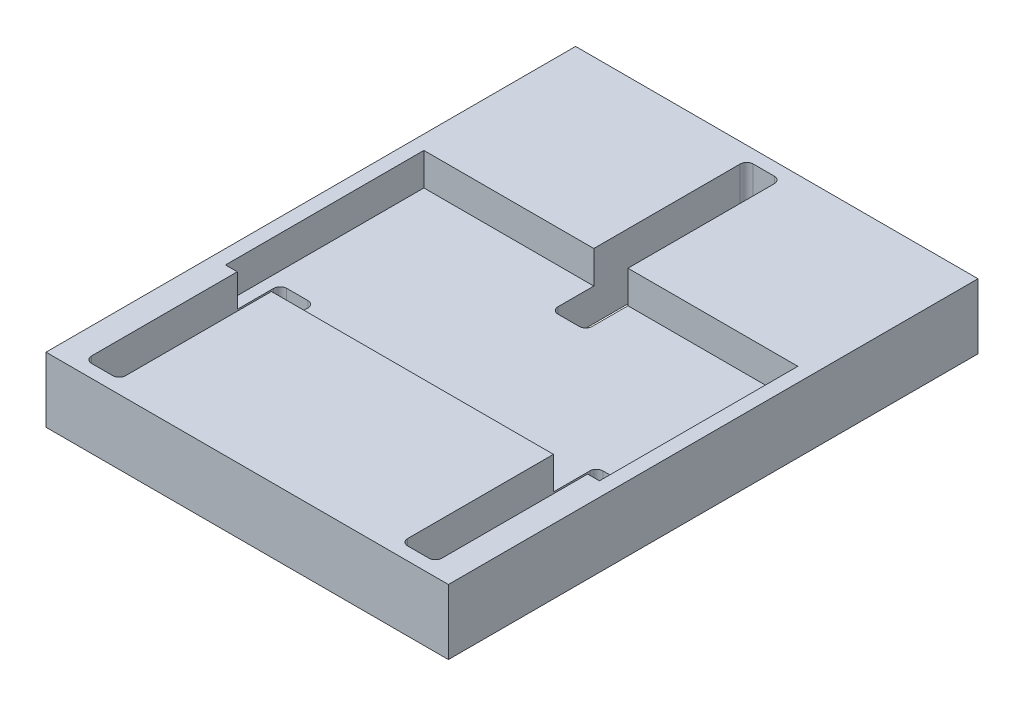
SolidWorks part; units mm, degrees
ref_plane "Front Plane" through (0, 0, 0) normal (0, 0, 1) x (1, 0, 0)
ref_plane "Top Plane" through (0, 0, 0) normal (0, 1, 0) x (1, 0, 0)
ref_plane "Right Plane" through (0, 0, 0) normal (1, 0, 0) x (0, 0, -1)
sketch "00 state" plane through (0, 0, 0) normal (0, 1, 0) x (1, 0, 0)
  line L0 (0, 0) -> (0, 15)
  line L1 (0, 15) -> (11.8, 31.1481)
  line L2 (11.8, 31.1481) -> (36.8, 31.1481)
  line L3 (36.8, 31.1481) -> (48.6, 15)
  line L4 (48.6, 15) -> (48.6, 0)
  line L5 (11.8, 31.1481) -> (24.3, 39.9007)
  line L6 (24.3, 39.9007) -> (36.8, 31.1481)
  line L7 (24.3, 39.9007) -> (24.3, 47.4007)
  line L8 (24.3, 47.4007) -> (24.3, 62.4007)
  dimension "D1" = 35
  dimension "D2" = 7.5
  dimension "D3" = 15
  dimension "D4" = 15
  dimension "D5" = 20
  dimension "D6" = 25
  dimension "D7" = 0
  dimension "D8" = 48.6
  dimension "D9" = 24.3
sketch "01 state" plane through (0, 0, 0) normal (0, 1, 0) x (1, 0, 0)
  line L0 (0, 0) -> (0, 15)
  line L1 (0, 15) -> (5.8095, 34.1377)
  line L2 (5.8095, 34.1377) -> (30.8095, 34.1377)
  line L3 (30.8095, 34.1377) -> (48.6, 25)
  line L4 (48.6, 25) -> (48.6, 10)
  line L5 (5.8095, 34.1377) -> (18.3095, 42.8903)
  line L6 (18.3095, 42.8903) -> (30.8095, 34.1377)
  line L7 (18.3095, 42.8903) -> (24.3, 47.4028)
  line L8 (24.3, 47.4028) -> (24.3, 62.4028)
  point P3 (37.9019, 64.6686)
  point P11 (0, 0)
  dimension "D1" = 35
  dimension "D2" = 7.5
  dimension "D3" = 15
  dimension "D4" = 15
  dimension "D5" = 20
  dimension "D6" = 25
  dimension "D7" = 48.6
  dimension "D8" = 24.3
  dimension "D9" = 10
sketch "10 state" plane through (0, 0, 0) normal (0, 1, 0) x (1, 0, 0)
  line L0 (0, 10) -> (0, 25)
  line L1 (0, 25) -> (17.7905, 34.1377)
  line L2 (17.7905, 34.1377) -> (42.7905, 34.1377)
  line L3 (42.7905, 34.1377) -> (48.6, 15)
  line L4 (48.6, 15) -> (48.6, 0)
  line L5 (17.7905, 34.1377) -> (30.2905, 42.8903)
  line L6 (30.2905, 42.8903) -> (42.7905, 34.1377)
  line L7 (30.2905, 42.8903) -> (24.3, 47.4028)
  line L8 (24.3, 47.4028) -> (24.3, 62.4028)
  point P3 (24.5104, 73.8516)
  dimension "D3" = 15
  dimension "D8" = 48.6
  dimension "D9" = 24.3
  dimension "D1" = 7.5
  dimension "D2" = 10
  dimension "D4" = 20
  dimension "D5" = 25
  dimension "D6" = 35
  dimension "D7" = 15
  dimension "D10" = 0
sketch "11 state" plane through (0, 0, 0) normal (0, 1, 0) x (1, 0, 0)
  line L0 (0, 10) -> (0, 25)
  line L1 (0, 25) -> (11.8, 41.1481)
  line L2 (11.8, 41.1481) -> (36.8, 41.1481)
  line L3 (36.8, 41.1481) -> (48.6, 25)
  line L4 (48.6, 25) -> (48.6, 10)
  line L5 (11.8, 41.1481) -> (24.3, 49.9007)
  line L6 (24.3, 49.9007) -> (36.8, 41.1481)
  line L7 (24.3, 49.9007) -> (24.3, 57.4007)
  line L8 (24.3, 57.4007) -> (24.3, 72.4007)
  point P3 (31.7394, 84.623)
  point P11 (66.091, 27.3101)
  dimension "D2" = 7.5
  dimension "D4" = 20
  dimension "D1" = 25
  dimension "D3" = 35
  dimension "D5" = 15
  dimension "D6" = 15
  dimension "D7" = 10
  dimension "D8" = 10
  dimension "D9" = 48.6
  dimension "D10" = 24.3
sketch "Sketch15" plane through (0, 0, 0) normal (0, 1, 0) x (1, 0, 0)
  line L0 (24.3, 76.9007) -> (-6.625, 76.9007)
  line L1 (-6.625, 76.9007) -> (-6.625, -4.5)
  line L2 (-6.625, -4.5) -> (24.3, -4.5)
  line L3 (24.3, -4.5) -> (24.3, 44.9007)
  line L4 (21.675, 72.4007) -> (21.675, 47.4007)
  line L5 (24.3, 44.9007) -> (21.675, 44.9007)
  line L6 (21.675, 44.9007) -> (21.675, 47.4007)
  line L7 (24.3, 74.9007) -> (21.675, 74.9007)
  line L8 (21.675, 74.9007) -> (21.675, 72.4007)
  line L9 (24.3, 69.7757) -> (24.3, 69.9007)
  line L10 (24.3, 74.9007) -> (24.3, 76.9007)
  line L11 (24.3, 49.9007) -> (24.3, 50.0257)
  line L12 (-2.625, 25) -> (-2.625, 0)
  line L13 (2.625, 25) -> (2.625, 0)
  line L14 (0, 27.5) -> (-2.625, 27.5)
  line L15 (-2.625, 27.5) -> (-2.625, 25)
  line L16 (0, 27.5) -> (2.625, 27.5)
  line L17 (2.625, 27.5) -> (2.625, 25)
  line L18 (0, -2.5) -> (2.625, -2.5)
  line L19 (2.625, -2.5) -> (2.625, 0)
  line L20 (0, -2.5) -> (-2.625, -2.5)
  line L21 (-2.625, -2.5) -> (-2.625, 0)
  circle A0 centre (24.3, 72.4007) radius 2.625 construction
  circle A1 centre (24.3, 72.4007) radius 2.5 construction
  circle A2 centre (24.3, 47.4007) radius 2.625 construction
  circle A3 centre (24.3, 47.4007) radius 2.5 construction
  circle A4 centre (0, 0) radius 2.625 construction
  circle A5 centre (0, 0) radius 2.5 construction
  circle A6 centre (0, 25) radius 2.625 construction
  circle A7 centre (0, 25) radius 2.5 construction
  point P39 (2.625, 25)
  dimension "D1" = 5.25
  dimension "D2" = 5
  dimension "D3" = 2
  dimension "D4" = 2
  dimension "D5" = 4
extrude "Boss-Extrude5" add sketch "Sketch15" along normal blind 10 contours L2 L3 L5 L6 L4 L8 L7 L10 L0 L1 | L13 L19 L18 L20 L21 L12 L15 L14 L16 L17
sketch "Sketch18" plane through (0, 10, 0) normal (0, 1, 0) x (1, 0, 0)
  line L0 (11.8, 41.1481) -> (11.8, 51.3981) construction
  line L1 (5.8095, 34.1377) -> (-4.4405, 34.1377) construction
  line L2 (11.8, 31.1481) -> (11.8, 20.8981) construction
  line L3 (21.675, 51.3981) -> (-4.4405, 51.3981)
  line L4 (21.675, 44.9007) -> (21.675, 74.9007) construction
  line L5 (-4.4405, 51.3981) -> (-4.4405, 20.8981)
  line L6 (-4.4405, 20.8981) -> (24.3, 20.8981)
  line L7 (24.3, -4.5) -> (24.3, 44.9007) construction
  line L8 (24.3, 20.8981) -> (24.3, 51.3981)
  line L10 (24.3, 51.3981) -> (21.675, 51.3981)
  point P13 (0, 0)
  dimension "D1" = 10.25
  dimension "D2" = 10.25
  dimension "D3" = 10.25
  dimension "D4" = 30.5
extrude "Cut-Extrude6" cut sketch "Sketch18" against normal blind 5
fillet "Fillet4" radius 1 6 edges at (2.625, 5, 2.5) (-2.625, 5, 2.5) (2.625, 2.5, -27.5) (-2.625, 2.5, -27.5) (21.675, 2.5, -44.9007) (21.675, 5, -74.9007)
mirror "Mirror25" about plane through (24.3, 10, 4.5) normal (-1, 0, 0) of "Fillet4", "Cut-Extrude6", "Boss-Extrude5"
sketch "Sketch19" plane through (0, 10, 0) normal (0, 1, 0) x (1, 0, 0)
  line L0 (2.625, 20.8981) -> (2.625, 26.5) construction
  line L1 (-1.625, 27.5) -> (1.625, 27.5) construction
  line L2 (-2.625, 26.5) -> (-2.625, 20.8981) construction
  line L3 (2.625, 21.1481) -> (2.625, 26.5)
  line L4 (-1.625, 27.5) -> (1.625, 27.5)
  line L5 (-2.625, 26.5) -> (-2.625, 21.1481)
  line L6 (-2.625, 21.1481) -> (-4.3405, 21.1481)
  line L7 (-4.3405, 21.1481) -> (-4.3405, 41.1481)
  line L8 (-4.3405, 41.1481) -> (24.3, 41.1481)
  line L9 (24.3, 41.1481) -> (24.3, 33.7731)
  line L10 (24.3, 21.1481) -> (2.625, 21.1481)
  line L11 (24.3, 76.9007) -> (24.3, 33.7731) construction
  line L12 (55.225, 76.9007) -> (-6.625, 76.9007) construction
  line L13 (-6.625, -4.5) -> (55.225, -4.5) construction
  line L14 (2.625, 20.8981) -> (45.975, 20.8981) construction
  line L15 (-4.4405, 51.3981) -> (-4.4405, 20.8981) construction
  line L16 (24.3, 31.1481) -> (-4.3405, 31.1481) construction
  line L17 (0.6595, 33.7731) -> (24.3, 33.7731)
  line L18 (0.6595, 28.5231) -> (24.3, 28.5231)
  line L19 (24.3, 28.5231) -> (24.3, 21.1481)
  line L20 (24.3, 28.5231) -> (24.3, -4.5) construction
  arc A0 (2.625, 26.5) -> (1.625, 27.5) centre (1.625, 26.5) ccw construction
  arc A1 (-1.625, 27.5) -> (-2.625, 26.5) centre (-1.625, 26.5) ccw construction
  arc A2 (2.625, 26.5) -> (1.625, 27.5) centre (1.625, 26.5) ccw
  arc A3 (-1.625, 27.5) -> (-2.625, 26.5) centre (-1.625, 26.5) ccw
  circle A4 centre (0.6595, 31.1481) radius 5 construction
  arc A5 (0.6595, 33.7731) -> (0.6595, 28.5231) centre (0.6595, 31.1481) ccw
  dimension "D4" = 10
  dimension "D5" = 5.25
  dimension "D1" = 0.25
  dimension "D2" = 0.1
  dimension "D3" = 20
  dimension "D6" = 10
extrude "Boss-Extrude6" [suppressed] add sketch "Sketch19" against normal blind 4.9 separate body
mirror "Mirror27" [suppressed]
equation "\"D9@00 state\" = \"D8@00 state\" / 2"
equation "\"D8@01 state\" = \"D7@01 state\" / 2"
equation "\"D9@10 state\" = \"D8@10 state\" / 2"
equation "\"D10@11 state\" = \"D9@11 state\" / 2"
equation "\"D6@Sketch19\"=\"D3@Sketch19\"/2"
